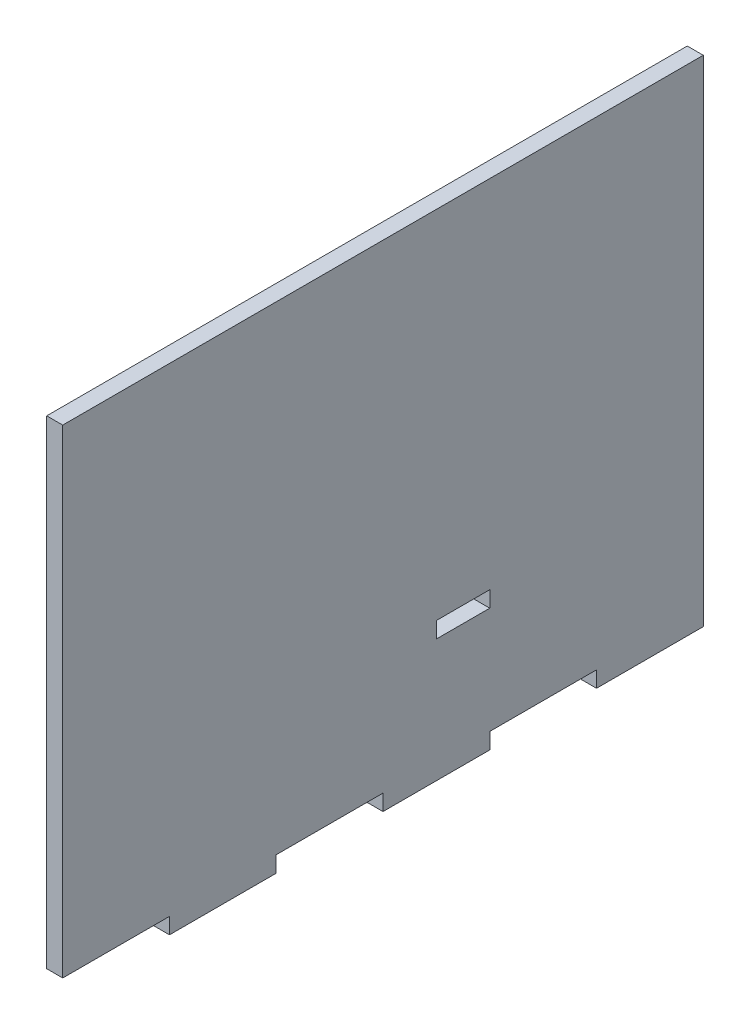
SolidWorks part; units mm, degrees
ref_plane "Alzado" through (0, 0, 0) normal (0, 0, 1) x (1, 0, 0)
ref_plane "Planta" through (0, 0, 0) normal (0, 1, 0) x (1, 0, 0)
ref_plane "Vista lateral" through (0, 0, 0) normal (1, 0, 0) x (0, 0, -1)
sketch "Croquis1" plane through (0, 0, 0) normal (1, 0, 0) x (0, 0, -1)
  line L0 (-60.5301, -78.6202) -> (-40.5301, -78.6202)
  line L1 (-20.5301, -78.6202) -> (-0.5301, -78.6202)
  line L2 (59.4699, -81.6202) -> (59.4699, 11.0869)
  line L3 (-40.5301, -78.6202) -> (-40.5301, -81.6202)
  line L4 (-60.5301, -78.6202) -> (-60.5301, 11.0869)
  line L5 (59.4699, -84.6631) -> (-60.5301, 85.3369) construction
  line L6 (59.4699, 85.3369) -> (-60.5301, -84.6631) construction
  line L7 (-40.5301, -81.6202) -> (-20.5301, -81.6202)
  line L8 (-20.5301, -81.6202) -> (-20.5301, -78.6202)
  line L9 (-0.5301, -78.6202) -> (-0.5301, -81.6202)
  line L10 (-0.5301, -81.6202) -> (19.4699, -81.6202)
  line L11 (19.4699, -81.6202) -> (19.4699, -78.6202)
  line L12 (19.4699, -78.6202) -> (39.4699, -78.6202)
  line L13 (39.4699, -78.6202) -> (39.4699, -81.6202)
  line L14 (39.4699, -81.6202) -> (59.4699, -81.6202)
  line L15 (59.4699, -81.6202) -> (59.4699, -78.6202)
  line L17 (-60.5301, 11.0869) -> (59.4699, 11.0869)
  line L18 (19.4699, -58.6202) -> (9.4699, -58.6202)
  line L19 (19.4699, -58.6202) -> (19.4699, -55.6202)
  line L20 (19.4699, -55.6202) -> (9.4699, -55.6202)
  line L21 (9.4699, -58.6202) -> (9.4699, -55.6202)
  line L22 (19.4699, -58.6202) -> (9.4699, -55.6202) construction
  line L23 (19.4699, -55.6202) -> (9.4699, -58.6202) construction
  point P0 (-0.5301, 0.3369)
  point P7 (14.4699, -57.1202)
  point P25 (29.4699, -78.6202)
  dimension "D2" = 89.7071
  dimension "D3" = 40
  dimension "D1" = 120
  dimension "D4" = 20
extrude "Saliente-Extruir1" add sketch "Croquis1" along normal blind 3 contours L17 L4 L0 L3 L7 L8 L1 L9 L10 L11 L12 L13 L14 L2
